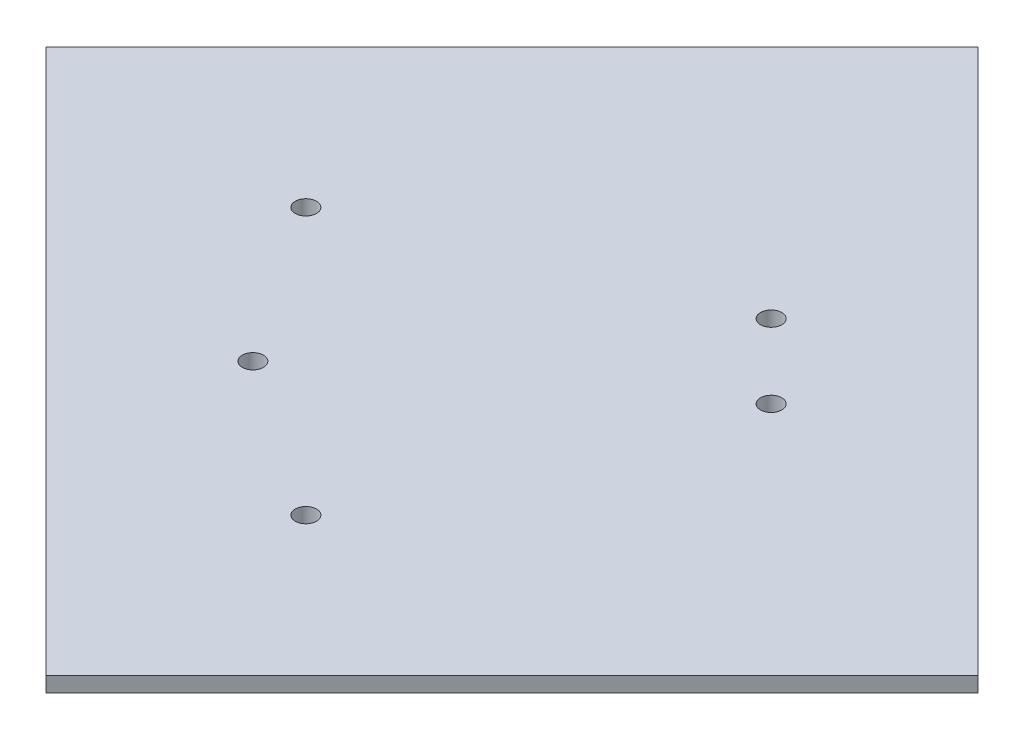
SolidWorks part; units mm, degrees
ref_plane "Front Plane" through (0, 0, 0) normal (0, 0, 1) x (1, 0, 0)
ref_plane "Top Plane" through (0, 0, 0) normal (0, 1, 0) x (1, 0, 0)
ref_plane "Right Plane" through (0, 0, 0) normal (1, 0, 0) x (0, 0, -1)
sketch "Sketch1" plane through (0, 0, 0) normal (0, 1, 0) x (-1, 0, 0)
  line L0 (17.6386, 17.6386) -> (24.9447, 10.3325) construction
  line L1 (24.9447, 10.3325) -> (90.0783, 37.3116) construction
  line L2 (90.0783, 37.3116) -> (68.9429, 68.9429) construction
  line L3 (68.9429, 68.9429) -> (37.3116, 90.0783) construction
  line L4 (37.3116, 90.0783) -> (10.3325, 24.9447) construction
  line L5 (17.6386, 17.6386) -> (68.9429, 68.9429) construction
  line L6 (24.9447, 10.3325) -> (17.6386, 17.6386) construction
  line L7 (10.3325, 24.9447) -> (-36.2751, 71.5523) construction
  line L8 (24.9447, 10.3325) -> (71.5523, -36.2751) construction
  line L10 (68.9429, 68.9429) -> (89.4179, 89.4179) construction
  line L11 (51.0773, -56.7501) -> (-56.7501, 51.0773)
  line L12 (-36.2751, 71.5523) -> (-56.7501, 51.0773)
  line L13 (71.5523, -36.2751) -> (51.0773, -56.7501)
  line L14 (35.5042, 143.3316) -> (143.3316, 35.5042)
  line L15 (71.5523, -36.2751) -> (143.3316, 35.5042)
  line L16 (-36.2751, 71.5523) -> (35.5042, 143.3316)
  line L17 (16.1526, 19.1246) -> (10.3325, 24.9447) construction
  circle A0 centre (24.9447, 10.3325) radius 2.1015
  circle A2 centre (10.3325, 24.9447) radius 2.1015
  circle A3 centre (90.0783, 37.3116) radius 2.1015
  circle A4 centre (68.9429, 68.9429) radius 2.1015
  circle A5 centre (37.3116, 90.0783) radius 2.1015
  dimension "D1" = 65.913
  dimension "D3" = 28.956
extrude "Boss-Extrude1" add sketch "Sketch1" along normal blind 3
